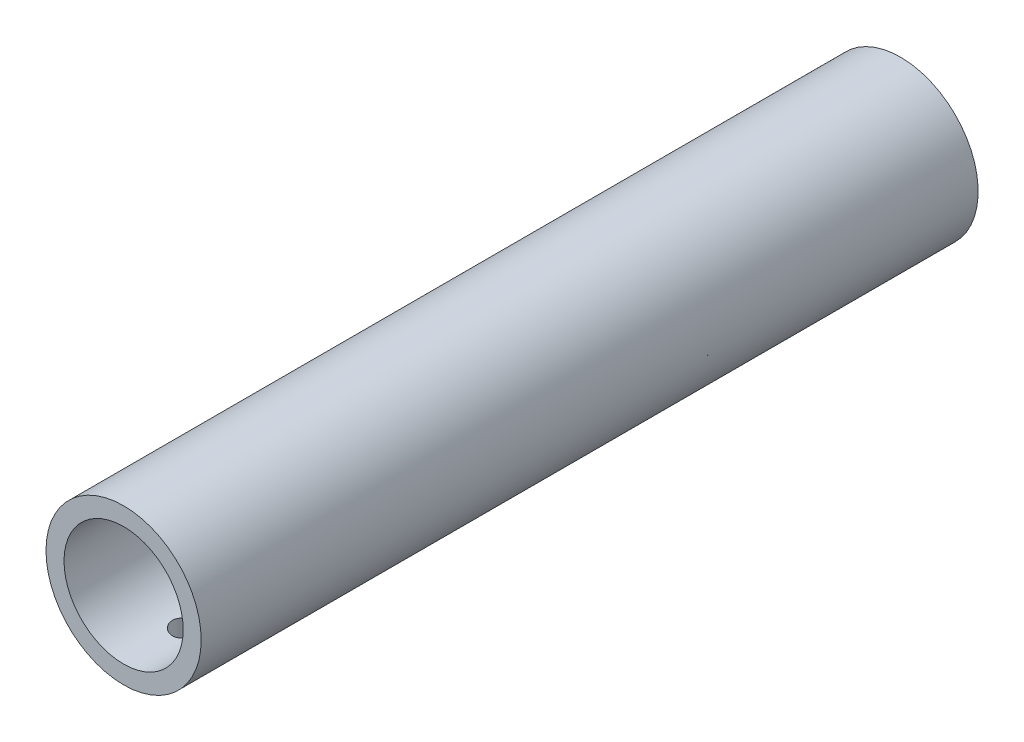
SolidWorks part; units mm, degrees
material "AISI 316 Stainless Steel Sheet (SS)"
ref_plane "Front Plane" through (0, 0, 0) normal (0, 0, 1) x (1, 0, 0)
ref_plane "Top Plane" through (0, 0, 0) normal (0, 1, 0) x (1, 0, 0)
ref_plane "Right Plane" through (0, 0, 0) normal (1, 0, 0) x (0, 0, -1)
sketch "Sketch1" plane through (0, 0, 0) normal (0, 0, 1) x (1, 0, 0)
  circle A0 centre (0, 0) radius 12.7
  circle A1 centre (0, 0) radius 9.75
  dimension "D1" = 25.4
  dimension "D2" = 19.5
extrude "Boss-Extrude1" add sketch "Sketch1" along normal blind 123
sketch "Sketch7" plane through (0, 0, 0) normal (0, 1, 0) x (1, 0, 0)
  line L0 (-12.7, -123) -> (12.7, -123) construction
  circle A0 centre (0, -10.17) radius 1.5
  circle A1 centre (0, -29) radius 1.5
  circle A2 centre (0, -113) radius 2
  dimension "D1" = 3
  dimension "D2" = 3
  dimension "D5" = 4
  dimension "D3" = 10.17
  dimension "D4" = 18.83
  dimension "D6" = 10
extrude "Cut-Extrude1" cut sketch "Sketch7" against normal blind 108
sketch "Sketch8" plane through (0, 0, 0) normal (0, 0, -1) x (-1, 0, 0)
  circle A0 centre (0, 0) radius 12.7
  circle A1 centre (0, 0) radius 9.75
extrude "Boss-Extrude2" add sketch "Sketch8" along normal blind 4.17
